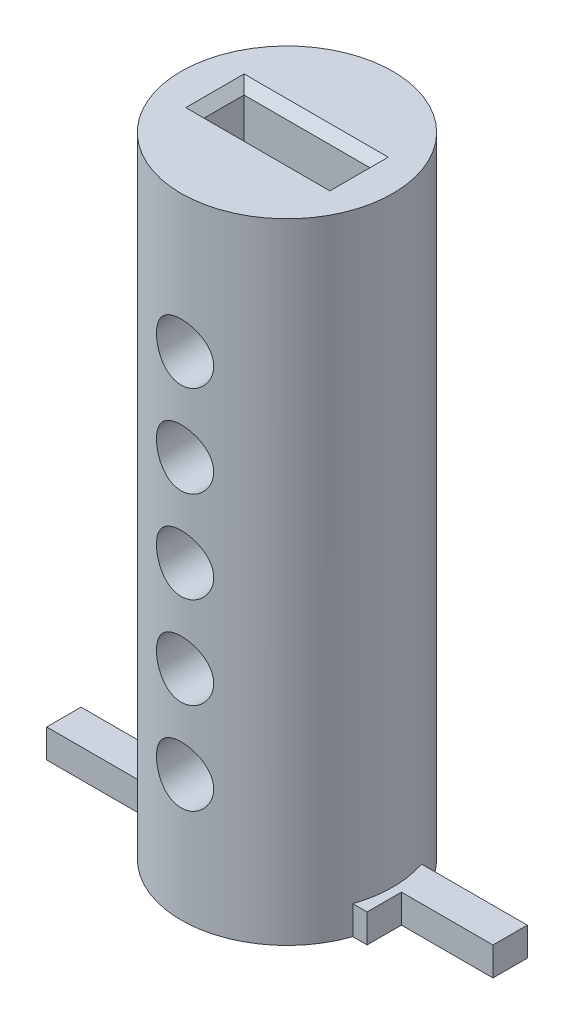
SolidWorks part; units mm, degrees
ref_plane "Front Plane" through (0, 0, 0) normal (0, 0, 1) x (1, 0, 0)
ref_plane "Top Plane" through (0, 0, 0) normal (0, 1, 0) x (1, 0, 0)
ref_plane "Right Plane" through (0, 0, 0) normal (1, 0, 0) x (0, 0, -1)
sketch "Sketch1" plane through (0, 0, 0) normal (0, 1, 0) x (1, 0, 0)
  circle A0 centre (0, 0) radius 9.25
  dimension "D1" = 18.5
extrude "Boss-Extrude1" add sketch "Sketch1" along normal blind 55
sketch "Sketch2" plane through (0, 55, 0) normal (0, 1, 0) x (1, 0, 0)
  line L1 (-5.5, -1.75) -> (5.5, -1.75)
  line L2 (-5.5, -1.75) -> (-5.5, 1.75)
  line L3 (-5.5, 1.75) -> (5.5, 1.75)
  line L4 (5.5, -1.75) -> (5.5, 1.75)
  line L5 (-5.5, -1.75) -> (5.5, 1.75) construction
  line L6 (-5.5, 1.75) -> (5.5, -1.75) construction
  point P0 (0, 0)
  dimension "D1" = 11
  dimension "D2" = 3.5
extrude "Cut-Extrude1" cut sketch "Sketch2" against normal blind 51
chamfer "Chamfer1" distance 0.8 angle 45 4 edges at (-5.5, 55, 0) (0, 55, 1.75) (5.5, 55, 0) (0, 55, -1.75)
ref_plane "Plane1" through (0, 0, 10) normal (0, 0, 1) x (1, 0, 0)
sketch "Sketch3" plane through (0, 0, 10) normal (0, 0, 1) x (1, 0, 0)
  line L0 (6.3, 55) -> (-6.3, 55) construction
  circle A0 centre (0, 43) radius 2.5
  circle A1 centre (0, 35) radius 2.5
  circle A2 centre (0, 27) radius 2.5
  circle A3 centre (0, 19) radius 2.5
  circle A4 centre (0, 11) radius 2.5
  dimension "D1" = 5
  dimension "D2" = 5
  dimension "D3" = 5
  dimension "D4" = 5
  dimension "D6" = 8
  dimension "D7" = 8
  dimension "D8" = 8
  dimension "D9" = 5
  dimension "D10" = 8
  dimension "D5" = 12
extrude "Cut-Extrude2" cut sketch "Sketch3" against normal blind 10
ref_plane "Plane2" through (18, 0, 0) normal (1, 0, 0) x (0, 0, -1)
ref_plane "Plane3" through (-18, 0, 0) normal (1, 0, 0) x (0, 0, -1)
sketch "Sketch5" plane through (18, 0, 0) normal (1, 0, 0) x (0, 0, -1)
  line L0 (-9.25, 0) -> (9.25, 0) construction
  line L1 (-3, 0) -> (3, 0)
  line L2 (-3, 0) -> (-3, 2.5)
  line L3 (-3, 2.5) -> (3, 2.5)
  line L4 (3, 0) -> (3, 2.5)
  dimension "D1" = 3
  dimension "D2" = 2.5
  dimension "D3" = 3
extrude "Boss-Extrude2" add sketch "Sketch5" against normal blind 20
sketch "Sketch6" plane through (-18, 0, 0) normal (1, 0, 0) x (0, 0, -1)
  line L0 (-9.25, 0) -> (9.25, 0) construction
  line L1 (3, 0) -> (-3, 0)
  line L2 (3, 0) -> (3, 2.5)
  line L3 (3, 2.5) -> (-3, 2.5)
  line L4 (-3, 0) -> (-3, 2.5)
  dimension "D1" = 2.5
  dimension "D2" = 3
  dimension "D3" = 3
extrude "Boss-Extrude3" add sketch "Sketch6" along normal blind 10
sketch "Sketch8" plane through (0, 0, 0) normal (0, -1, 0) x (1, 0, 0)
  line L1 (18, 3) -> (10, 3)
  line L2 (18, 3) -> (18, 0)
  line L3 (18, 0) -> (10, 0)
  line L4 (10, 3) -> (10, 0)
  line L5 (-18, -3) -> (-10, -3)
  line L6 (-18, -3) -> (-18, 0)
  line L7 (-18, 0) -> (-10, 0)
  line L8 (-10, -3) -> (-10, 0)
  dimension "D1" = 8
  dimension "D2" = 8
extrude "Cut-Extrude3" cut sketch "Sketch8" against normal blind 10
